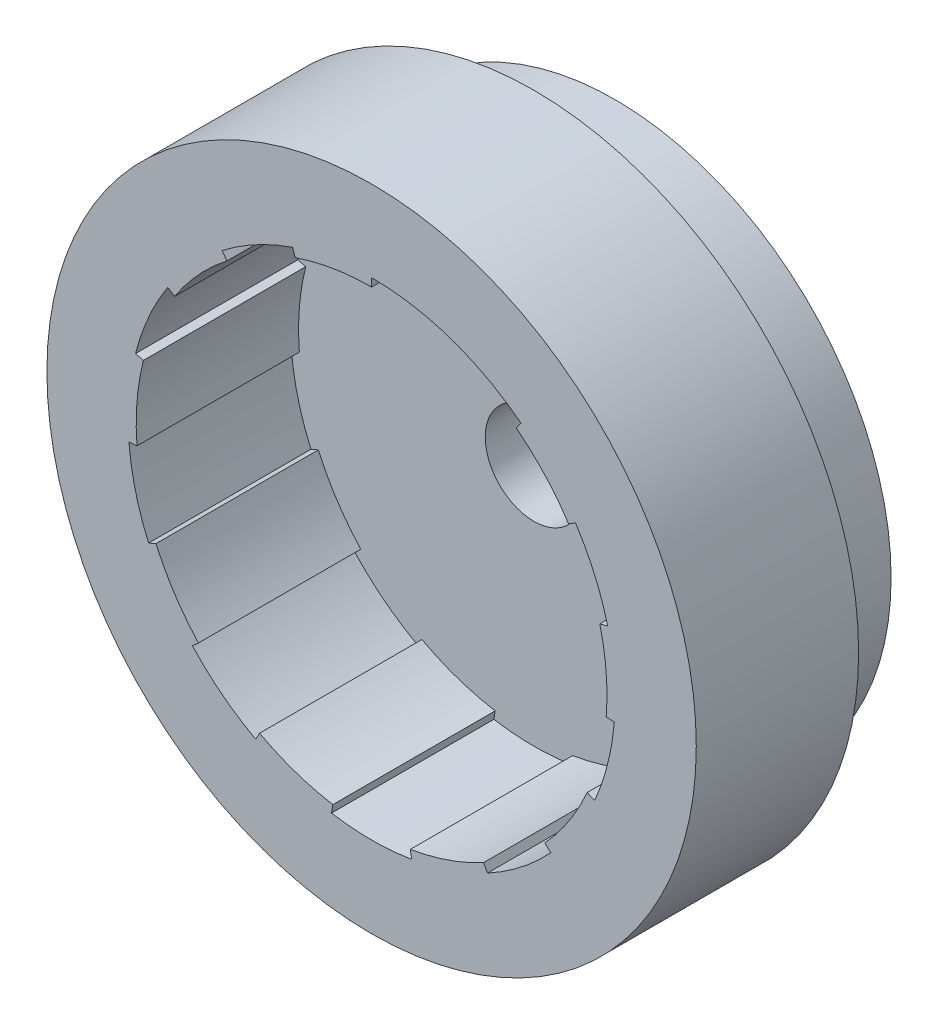
SolidWorks part; units mm, degrees
ref_plane "Front Plane" through (0, 0, 0) normal (0, 0, 1) x (1, 0, 0)
ref_plane "Top Plane" through (0, 0, 0) normal (0, 1, 0) x (1, 0, 0)
ref_plane "Right Plane" through (0, 0, 0) normal (1, 0, 0) x (0, 0, -1)
sketch "Sketch1" plane through (0, 0, 0) normal (0, 0, 1) x (1, 0, 0)
  line L0 (0, 0) -> (0, 15)
  line L1 (0, 0) -> (4.8705, 14.1873)
  line L2 (0, 0) -> (9.2132, 11.8371)
  line L3 (0, 0) -> (12.5575, 8.2042)
  line L4 (0, 0) -> (14.541, 3.6823)
  line L5 (0, 0) -> (14.9488, -1.2387)
  line L6 (0, 0) -> (13.7366, -6.0254)
  line L7 (0, 0) -> (11.0359, -10.1592)
  line L8 (0, 0) -> (7.1392, -13.1921)
  line L9 (0, 0) -> (2.4689, -14.7954)
  line L10 (0, 0) -> (-2.4689, -14.7954)
  line L11 (0, 0) -> (-7.1392, -13.1921)
  line L12 (0, 0) -> (-11.0359, -10.1592)
  line L13 (0, 0) -> (-13.7366, -6.0254)
  line L14 (0, 0) -> (-14.9488, -1.2387)
  line L15 (0, 0) -> (-14.541, 3.6823)
  line L16 (0, 0) -> (-12.5575, 8.2042)
  line L17 (0, 0) -> (-9.2132, 11.8371)
  line L18 (0, 0) -> (-4.8705, 14.1873)
  circle A0 centre (0, 0) radius 15
  circle A1 centre (0, 0) radius 14.5
  circle A2 centre (0, 0) radius 20
  point P27 (0, 0)
  dimension "D1" = 30
  dimension "D2" = 29
  dimension "D3" = 40
  dimension "D4" = 19
extrude "Boss-Extrude2" add sketch "Sketch1" along normal blind 10 contours A2 A0 | A1 L0 A0 L18 | A1 L3 A0 L2 | A1 L5 A0 L4 | A1 L7 A0 L6 | A1 L9 A0 L8 | A1 L11 A0 L10 | A1 L13 A0 L12 | A1 L15 A0 L14 | A1 L17 A0 L16
sketch "Sketch2" plane through (0, 0, 0) normal (0, 0, 1) x (1, 0, 0)
  circle A0 centre (0, 0) radius 17
  dimension "D1" = 34
extrude "Boss-Extrude4" add sketch "Sketch2" against normal blind 5
sketch "Sketch5" plane through (0, 0, -5) normal (0, 0, -1) x (-1, 0, 0)
  circle A0 centre (0, 0) radius 3
  dimension "D1" = 6
extrude "Cut-Extrude2" cut sketch "Sketch5" against normal through all
